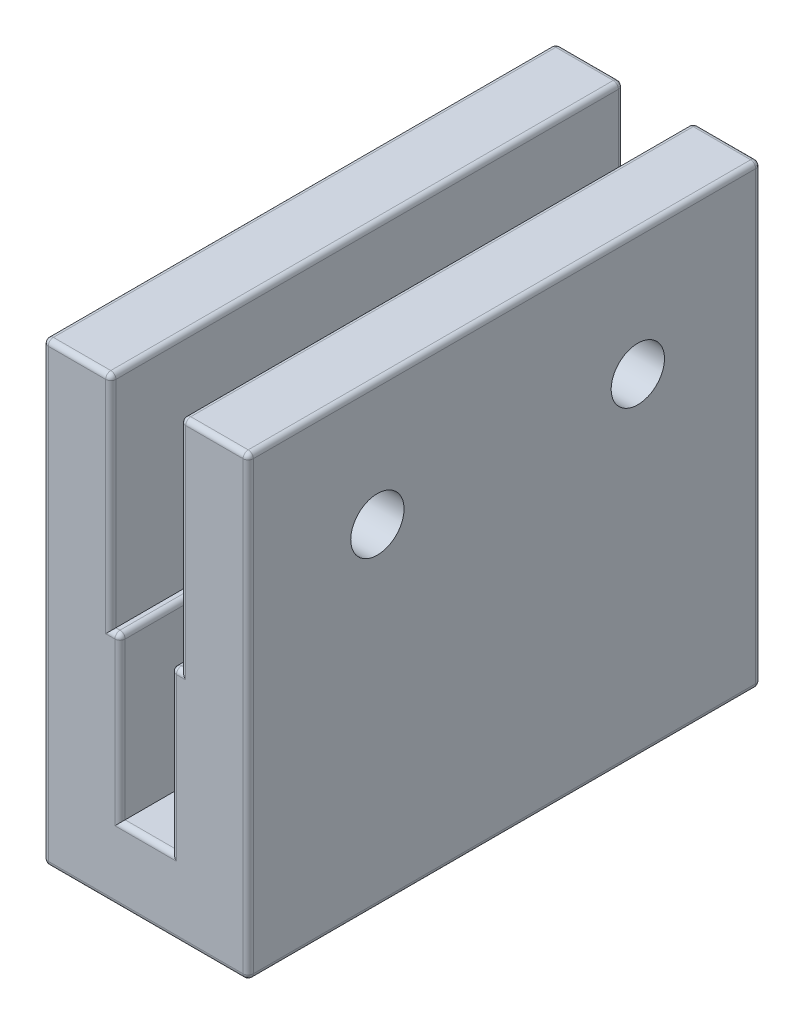
SolidWorks part; units mm, degrees
ref_plane "Front Plane" through (0, 0, 0) normal (0, 0, 1) x (1, 0, 0)
ref_plane "Top Plane" through (0, 0, 0) normal (0, 1, 0) x (1, 0, 0)
ref_plane "Right Plane" through (0, 0, 0) normal (1, 0, 0) x (0, 0, -1)
sketch "Sketch2" plane through (0, 0, 0) normal (0, 1, 0) x (1, 0, 0)
  line L1 (-10, 25) -> (10, 25)
  line L2 (-10, 25) -> (-10, -25)
  line L3 (-10, -25) -> (10, -25)
  line L4 (10, 25) -> (10, -25)
  line L5 (-10, 25) -> (10, -25) construction
  line L6 (-10, -25) -> (10, 25) construction
  point P1 (0, 0)
  dimension "D1" = 20
  dimension "D2" = 50
extrude "Boss-Extrude1" add sketch "Sketch2" along normal blind 44.5
sketch "Sketch3" plane through (0, 0, 25) normal (0, 0, 1) x (1, 0, 0)
  line L0 (-10, 44.5) -> (10, 44.5) construction
  line L1 (-3.4, 44.5) -> (3.4, 44.5)
  line L2 (-3.4, 44.5) -> (-3.4, 23.02)
  line L3 (-3.4, 23.02) -> (3.4, 23.02)
  line L4 (3.4, 44.5) -> (3.4, 23.02)
  line L7 (-2.5, 7.25) -> (2.5, 7.25)
  line L8 (-2.5, 7.25) -> (-2.5, 23.02)
  line L9 (-2.5, 23.02) -> (2.5, 23.02)
  line L10 (2.5, 7.25) -> (2.5, 23.02)
  point P8 (0, 23.02)
  point P12 (0, 23.02)
  dimension "D1" = 6.8
  dimension "D2" = 21.48
  dimension "D3" = 5
  dimension "D4" = 15.77
extrude "Cut-Extrude3" cut sketch "Sketch3" against normal through all contours L10 L9 L8 L7 | L2 L3 L4 L1
sketch "Sketch7" plane through (-10, 0, 0) normal (-1, 0, 0) x (0, 0, 1)
  line L0 (-25, 0) -> (25, 0) construction
  line L1 (-18.6, 3.48) -> (-14, 3.48)
  line L2 (-18.6, 3.48) -> (-18.6, 23.58)
  line L3 (-18.6, 23.58) -> (-14, 23.58)
  line L4 (-14, 3.48) -> (-14, 23.58)
  line L5 (-25, 44.5) -> (-25, 0) construction
  line L6 (0, 44.5) -> (0, 0) construction
  line L7 (-25, 44.5) -> (25, 44.5) construction
  line L8 (18.6, 23.58) -> (14, 23.58)
  line L9 (14, 3.48) -> (14, 23.58)
  line L10 (18.6, 3.48) -> (14, 3.48)
  line L11 (18.6, 3.48) -> (18.6, 23.58)
  dimension "D1" = 3.48
  dimension "D2" = 20.1
  dimension "D3" = 4.6
  dimension "D4" = 6.4
fillet "Fillet1" radius 0.5 32 edges at (-10, 0, 0) (10, 0, 0) (-10, 22.25, -25) (0, 0, -25) (10, 22.25, -25) (3.4, 33.76, -25) (2.95, 23.02, -25) (2.5, 15.135, -25) (0, 7.25, -25) (-2.5, 15.135, -25) (-2.95, 23.02, -25) (-3.4, 33.76, -25) (-2.5, 15.135, 25) (0, 7.25, 25) (2.5, 15.135, 25) (2.95, 23.02, 25) (3.4, 33.76, 25) (10, 22.25, 25) (0, 0, 25) (-10, 22.25, 25) (-3.4, 33.76, 25) (-2.95, 23.02, 25) (10, 44.5, 0) (6.7, 44.5, 25) (3.4, 44.5, 0) (6.7, 44.5, -25) (-6.7, 44.5, 25) (-10, 44.5, 0) (-6.7, 44.5, -25) (-3.4, 44.5, 0) (2.5, 23.02, 0) (-2.5, 23.02, 0)
extrude "Cut-Extrude4" cut sketch "Sketch7" against normal blind 3.25 contours L9 L8 L11 L10
sketch "Sketch8" plane through (-10, 0, 0) normal (-1, 0, 0) x (0, 0, 1)
  line L0 (-25, 0) -> (25, 0) construction
  line L1 (-25, 44.5) -> (-25, 0) construction
  circle A0 centre (-13, 32.41) radius 2.6
  circle A1 centre (12.4, 32.41) radius 2.6
  dimension "D2" = 5.2
  dimension "D1" = 32.41
  dimension "D3" = 12
  dimension "D4" = 25.4
extrude "Cut-Extrude5" cut sketch "Sketch8" against normal through all and the other way through all
